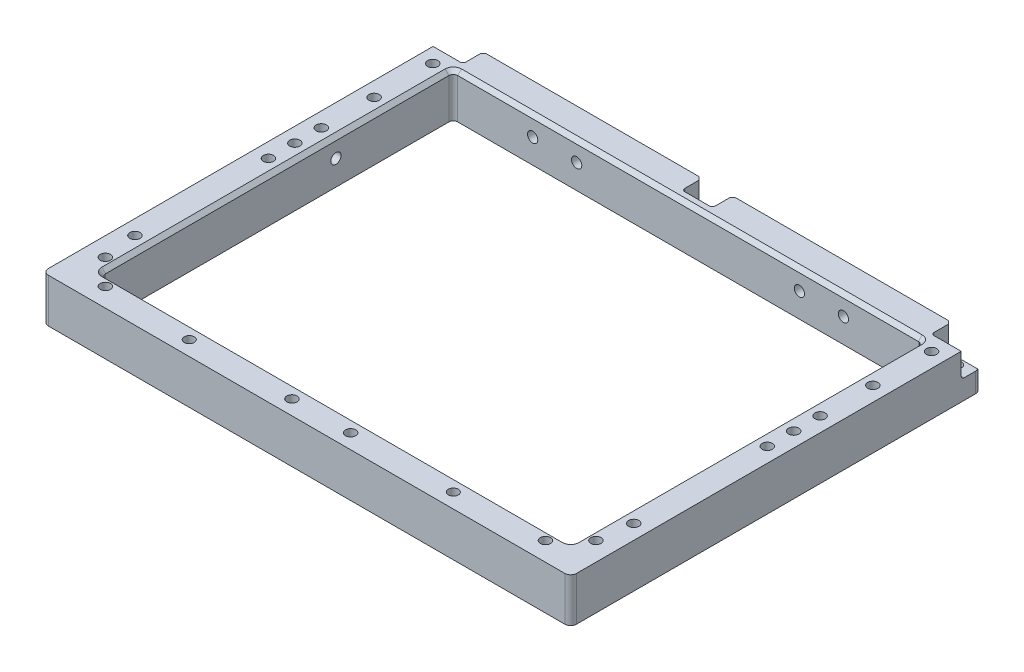
SolidWorks part; units mm, degrees
material "PLA"
ref_plane "Front Plane" through (0, 0, 0) normal (0, 0, 1) x (1, 0, 0)
ref_plane "Top Plane" through (0, 0, 0) normal (0, 1, 0) x (1, 0, 0)
ref_plane "Right Plane" through (0, 0, 0) normal (1, 0, 0) x (0, 0, -1)
sketch "Sketch1" plane through (0, 0, 0) normal (0, 1, 0) x (1, 0, 0)
  line L1 (-114.3, 88.9) -> (114.3, 88.9)
  line L2 (-114.3, 88.9) -> (-114.3, -88.9)
  line L3 (-114.3, -88.9) -> (114.3, -88.9)
  line L4 (114.3, 88.9) -> (114.3, -88.9)
  line L5 (-114.3, 88.9) -> (114.3, -88.9) construction
  line L6 (-114.3, -88.9) -> (114.3, 88.9) construction
  line L7 (-101.6, 76.2) -> (101.6, 76.2)
  line L8 (-101.6, 76.2) -> (-101.6, -76.2)
  line L9 (-101.6, -76.2) -> (101.6, -76.2)
  line L10 (101.6, 76.2) -> (101.6, -76.2)
  line L11 (-101.6, 76.2) -> (101.6, -76.2) construction
  line L12 (-101.6, -76.2) -> (101.6, 76.2) construction
  point P0 (0, 0)
  point P6 (0, 0)
  dimension "D1" = 177.8
  dimension "D2" = 152.4
  dimension "D3" = 228.6
  dimension "D4" = 203.2
extrude "Boss-Extrude1" add sketch "Sketch1" along normal blind 19.05
sketch "Sketch2" plane through (0, 0, -88.9) normal (0, 0, -1) x (-1, 0, 0)
  line L0 (114.3, 19.05) -> (114.3, 8.509)
  line L1 (114.3, 19.05) -> (114.3, 0) construction
  line L2 (114.3, 8.509) -> (101.346, 8.509)
  line L3 (101.346, 8.509) -> (101.346, 19.05)
  line L4 (-114.3, 19.05) -> (114.3, 19.05) construction
  line L5 (101.346, 19.05) -> (114.3, 19.05)
  line L6 (0, 0) -> (0, 19.05) construction
  line L7 (-6.604, 19.05) -> (6.604, 19.05)
  line L8 (6.604, 19.05) -> (6.604, 8.509)
  line L9 (6.604, 8.509) -> (-6.604, 8.509)
  line L11 (-6.604, 19.05) -> (-6.604, 8.509)
  line L12 (-101.346, 19.05) -> (-114.3, 19.05)
  line L13 (-101.346, 8.509) -> (-101.346, 19.05)
  line L14 (-114.3, 8.509) -> (-101.346, 8.509)
  line L15 (-114.3, 19.05) -> (-114.3, 8.509)
  point P16 (0, 8.509)
  dimension "D1" = 10.541
  dimension "D2" = 12.954
  dimension "D3" = 10.541
  dimension "D4" = 13.208
extrude "Cut-Extrude1" cut sketch "Sketch2" against normal blind 8.763
sketch "Sketch3" plane through (0, 8.509, 0) normal (0, 1, 0) x (1, 0, 0)
  line L0 (0, 88.9) -> (0, 80.137) construction
  line L1 (6.604, 88.9) -> (-6.604, 88.9) construction
  line L2 (-6.604, 80.137) -> (6.604, 80.137) construction
  line L3 (-107.823, 80.137) -> (-107.823, 88.9) construction
  line L4 (-114.3, 80.137) -> (-101.346, 80.137) construction
  line L5 (-101.346, 88.9) -> (-114.3, 88.9) construction
  circle A0 centre (-107.823, 84.5185) radius 2.2225
  circle A1 centre (0, 84.5185) radius 2.2225
  circle A2 centre (107.823, 84.5185) radius 2.2225
  dimension "D1" = 4.445
  dimension "D2" = 4.445
extrude "Front-Base-MountHoles" cut sketch "Sketch3" against normal blind 7.112
fillet "Fillet2" radius 1.27 11 edges at (101.346, 8.509, -84.5185) (107.823, 8.509, -80.137) (-6.604, 8.509, -84.5185) (0, 8.509, -80.137) (6.604, 8.509, -84.5185) (-107.823, 8.509, -80.137) (-101.346, 8.509, -84.5185) (-101.346, 13.7795, -80.137) (-6.604, 13.7795, -80.137) (6.604, 13.7795, -80.137) (101.346, 13.7795, -80.137)
chamfer "Chamfer1" distance 1.27 angle 45 11 edges at (-108.458, 8.509, -88.9) (-101.718, 8.881, -88.9) (-101.346, 14.4145, -88.9) (-6.604, 14.4145, -88.9) (-6.232, 8.881, -88.9) (0, 8.509, -88.9) (6.232, 8.881, -88.9) (6.604, 14.4145, -88.9) (108.458, 8.509, -88.9) (101.718, 8.881, -88.9) (101.346, 14.4145, -88.9)
sketch "Sketch4" plane through (0, 0, -88.9) normal (0, 0, -1) x (-1, 0, 0)
  line L0 (0, 0) -> (0, 19.05) construction
  line L1 (-114.3, 0) -> (114.3, 0) construction
  line L2 (5.334, 19.05) -> (-5.334, 19.05) construction
  circle A0 centre (-20.32, 9.525) radius 2.2225
  circle A1 centre (-81.28, 9.525) radius 2.2225
  circle A2 centre (81.28, 9.525) radius 2.2225
  circle A3 centre (20.32, 9.525) radius 2.2225
  dimension "D1" = 4.445
  dimension "D2" = 4.445
  dimension "D3" = 20.32
  dimension "D4" = 81.28
  dimension "D5" = 9.525
  dimension "D6" = 9.525
extrude "Front-base-MountHoles2" cut sketch "Sketch4" against normal blind 7.62
sketch "Sketch5" plane through (0, 19.05, 0) normal (0, 1, 0) x (1, 0, 0)
  line L0 (-114.3, 80.137) -> (-114.3, -88.9) construction
  line L1 (-114.3, -88.9) -> (114.3, -88.9) construction
  line L2 (0, 0) -> (0, -50000) construction
  circle A0 centre (-95.25, -80.772) radius 2.2225
  circle A1 centre (-106.172, -69.85) radius 2.2225
  circle A2 centre (106.172, -69.85) radius 2.2225
  circle A3 centre (95.25, -80.772) radius 2.2225
  dimension "D1" = 4.445
  dimension "D2" = 4.445
  dimension "D3" = 8.128
  dimension "D4" = 8.128
  dimension "D5" = 19.05
  dimension "D6" = 19.05
extrude "Rear-Wall-MountHoles" cut sketch "Sketch5" against normal blind 7.62
fillet "Fillet3" radius 1.905 4 edges at (-101.6, 9.525, 76.2) (101.6, 9.525, 76.2) (101.6, 9.525, -76.2) (-101.6, 9.525, -76.2)
sketch "Sketch6" plane through (0, 19.05, 0) normal (0, 1, 0) x (1, 0, 0)
  line L0 (114.3, -88.9) -> (114.3, 80.137) construction
  line L1 (-99.695, -76.2) -> (99.695, -76.2) construction
  line L2 (101.6, -74.295) -> (101.6, 74.295) construction
  line L3 (0, 0) -> (0, -76.2) construction
  circle A0 centre (107.95, -55.245) radius 2.2225
  circle A1 centre (107.95, 2.54) radius 2.2225
  circle A2 centre (107.95, 13.97) radius 2.2225
  circle A3 centre (107.95, 25.4) radius 2.2225
  circle A8 centre (-107.95, 25.4) radius 2.2225
  circle A9 centre (-107.95, 13.97) radius 2.2225
  circle A10 centre (-107.95, 2.54) radius 2.2225
  circle A11 centre (-107.95, -55.245) radius 2.2225
  dimension "D1" = 4.445
  dimension "D4" = 4.445
  dimension "D5" = 4.445
  dimension "D6" = 4.445
  dimension "D2" = 6.35
  dimension "D3" = 20.955
  dimension "D7" = 78.74
  dimension "D8" = 90.17
  dimension "D9" = 101.6
  dimension "D10" = 6.35
  dimension "D11" = 6.35
  dimension "D12" = 6.35
extrude "Motor_Mount_Holes" cut sketch "Sketch6" against normal blind 7.366
chamfer "Chamfer2" distance 1.651 angle 45 8 edges at (-101.6, 19.05, 0) (-101.042, 19.05, 75.642) (-101.042, 19.05, -75.642) (0, 19.05, 76.2) (0, 19.05, -76.2) (101.042, 19.05, 75.642) (101.042, 19.05, -75.642) (101.6, 19.05, 0)
sketch "Sketch7" plane through (0, 19.05, 0) normal (0, 1, 0) x (1, 0, 0)
  line L0 (0, 0) -> (0, -88.9) construction
  line L1 (-114.3, -88.9) -> (114.3, -88.9) construction
  line L2 (-12.7, -76.2) -> (-12.7, -88.9) construction
  line L4 (-99.695, -76.2) -> (99.695, -76.2) construction
  circle A0 centre (-12.7, -82.55) radius 2.2225
  circle A1 centre (12.7, -82.55) radius 2.2225
  dimension "D1" = 4.445
  dimension "D2" = 12.7
extrude "RearBrace_MountHoles" cut sketch "Sketch7" against normal blind 7.62
sketch "Sketch8" plane through (0, 19.05, 0) normal (0, 1, 0) x (1, 0, 0)
  line L0 (114.3, 60.96) -> (101.6, 60.96) construction
  line L1 (114.3, -88.9) -> (114.3, 80.137) construction
  line L2 (101.6, -74.295) -> (101.6, 74.295) construction
  line L3 (107.95, 60.96) -> (107.95, 73.66) construction
  line L4 (-99.695, -76.2) -> (99.695, -76.2) construction
  line L5 (0, 0) -> (0, -88.9) construction
  line L6 (-114.3, -88.9) -> (114.3, -88.9) construction
  line L7 (-107.95, 60.96) -> (-107.95, 73.66) construction
  line L8 (-114.3, 60.96) -> (-101.6, 60.96) construction
  circle A0 centre (107.95, 73.66) radius 2.2225
  circle A1 centre (107.95, 48.26) radius 2.2225
  circle A2 centre (-107.95, 48.26) radius 2.2225
  circle A3 centre (-107.95, 73.66) radius 2.2225
  dimension "D1" = 4.445
  dimension "D2" = 25.4
  dimension "D3" = 137.16
extrude "SideBrace_MountHoles" cut sketch "Sketch8" against normal blind 7.112
sketch "Sketch9" plane through (0, 19.05, 0) normal (0, 1, 0) x (1, 0, 0)
  line L0 (0, -88.9) -> (0, -76.2) construction
  line L1 (-114.3, -88.9) -> (114.3, -88.9) construction
  line L2 (-99.695, -76.2) -> (99.695, -76.2) construction
  line L3 (0, -82.55) -> (-57.15, -82.55) construction
  circle A0 centre (-57.15, -82.55) radius 2.159
  circle A1 centre (57.15, -82.55) radius 2.159
  dimension "D1" = 4.318
  dimension "D2" = 114.3
extrude "BatteryMount_Holes" cut sketch "Sketch9" against normal blind 8.89
fillet "Fillet4" radius 2.54 4 edges at (-114.3, 3.6195, -88.9) (114.3, 3.6195, -88.9) (-114.3, 9.525, 88.9) (114.3, 9.525, 88.9)
sketch "Sketch10" plane through (0, 0, -76.2) normal (0, 0, 1) x (1, 0, 0)
  line L0 (0, 0) -> (0, 50000) construction
  line L1 (-111.76, 0) -> (111.76, 0) construction
  line L2 (101.6, 17.399) -> (101.6, 0) construction
  line L3 (48.2067, 10.541) -> (67.2567, 10.541) construction
  line L4 (99.695, 0) -> (-99.695, 0) construction
  line L5 (-48.2067, 10.541) -> (-67.2567, 10.541) construction
  circle A0 centre (48.2067, 10.541) radius 2.2225
  circle A1 centre (67.2567, 10.541) radius 2.2225
  circle A2 centre (-67.2567, 10.541) radius 2.2225
  circle A3 centre (-48.2067, 10.541) radius 2.2225
  point P4 (0, 0)
  dimension "D3" = 4.445
  dimension "D1" = 19.05
  dimension "D2" = 34.3433
  dimension "D4" = 10.541
extrude "Motor-Brace-MountHoles" cut sketch "Sketch10" against normal blind 5.588
sketch "Sketch11" plane through (101.6, 0, 0) normal (-1, 0, 0) x (0, 0, 1)
  line L0 (76.2, 17.399) -> (76.2, 0) construction
  line L1 (76.2, 17.399) -> (76.2, 0) construction
  line L2 (-80.137, 19.05) -> (86.36, 19.05) construction
  circle A0 centre (-25.4, 10.795) radius 2.2225
  dimension "D1" = 4.445
  dimension "D2" = 101.6
  dimension "D3" = 8.255
extrude "DriveTrain-Brace2Hole" cut sketch "Sketch11" against normal blind 7.239
mirror "Mirror1" about plane through (0, 0, 0) normal (1, 0, 0) of "DriveTrain-Brace2Hole"
equation "\"D2@Sketch3\"=\"D1@Sketch3\""
equation "\"D2@Sketch5\"=\"D1@Sketch5\""
equation "\"D4@Sketch6\"=\"D1@Sketch6\""
equation "\"D5@Sketch6\"=\"D1@Sketch6\""
equation "\"D6@Sketch6\"=\"D1@Sketch6\""
equation "\"D10@Sketch6\"=\"D2@Sketch6\""
equation "\"D11@Sketch6\"=\"D2@Sketch6\""
equation "\"D12@Sketch6\"=\"D2@Sketch6\""
equation "\"D1@Sketch2\"=\"D3@Sketch2\""
equation "\"D1@Sketch4\"=\"D2@Sketch4\""
